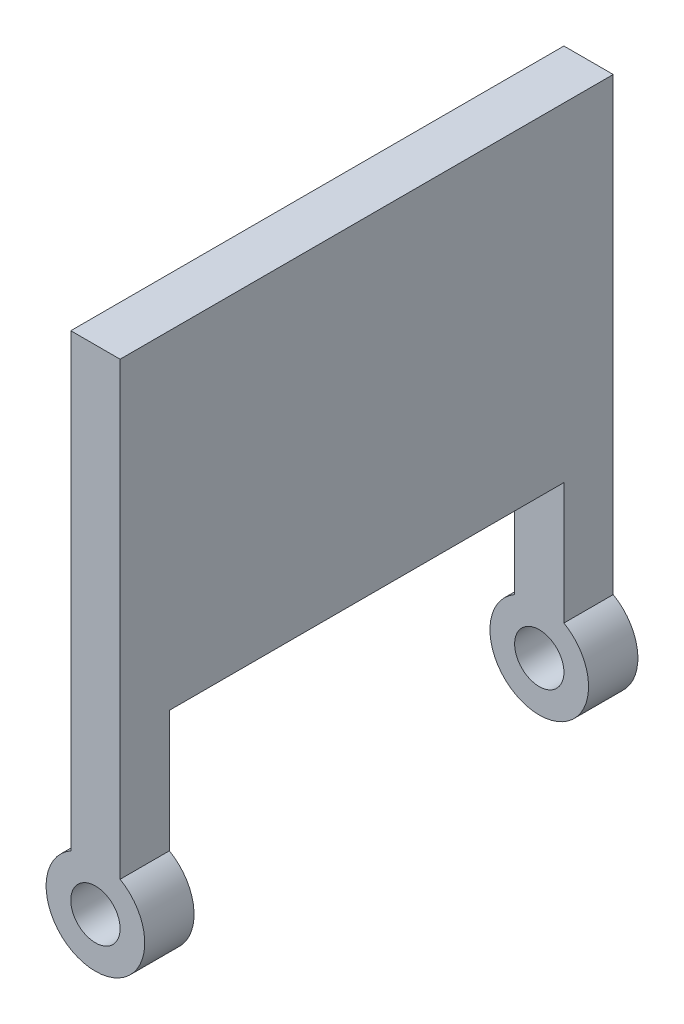
SolidWorks part; units mm, degrees
ref_plane "Front" through (0, 0, 0) normal (0, 0, 1) x (1, 0, 0)
ref_plane "Top" through (0, 0, 0) normal (0, 1, 0) x (1, 0, 0)
ref_plane "Right" through (0, 0, 0) normal (1, 0, 0) x (0, 0, -1)
sketch "Croquis1" plane through (0, 0, 0) normal (0, 0, 1) x (1, 0, 0)
  line L0 (0, 0) -> (0, 60) construction
  line L1 (3, 60) -> (-3, 60)
  line L2 (-3, 60) -> (-3, 5.1962)
  line L3 (3, 60) -> (3, 5.1962)
  circle A0 centre (0, 0) radius 3
  arc A1 (-3, 5.1962) -> (3, 5.1962) centre (0, 0) ccw
  dimension "D1" = 6
  dimension "D2" = 12
  dimension "D3" = 3
  dimension "D4" = 60
extrude "Saliente-Extruir1" add sketch "Croquis1" along normal blind 6
sketch "Croquis2" plane through (0, 0, 6) normal (0, 0, 1) x (1, 0, 0)
  line L0 (3, 5.1962) -> (3, 60) construction
  line L1 (-3, 60) -> (3, 60)
  line L2 (-3, 60) -> (-3, 20)
  line L3 (-3, 20) -> (3, 20)
  line L4 (3, 60) -> (3, 20)
  dimension "D1" = 40
extrude "Saliente-Extruir2" add sketch "Croquis2" along normal blind 48
sketch "Croquis3" plane through (0, 0, 54) normal (0, 0, 1) x (1, 0, 0)
  line L0 (-3, 5.1962) -> (-3, 60)
  line L1 (-3, 60) -> (3, 60)
  line L2 (3, 60) -> (3, 5.1962)
  circle A0 centre (0, 0) radius 3
  arc A1 (-3, 5.1962) -> (3, 5.1962) centre (0, 0) ccw
extrude "Saliente-Extruir3" add sketch "Croquis3" along normal blind 6
